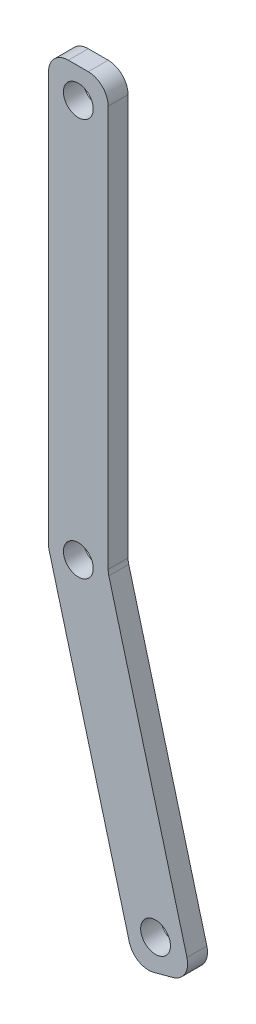
SolidWorks part; units mm, degrees
material "ABS"
ref_plane "Plan de face" through (0, 0, 0) normal (0, 0, 1) x (1, 0, 0)
ref_plane "Plan de dessus" through (0, 0, 0) normal (0, 1, 0) x (1, 0, 0)
ref_plane "Plan de droite" through (0, 0, 0) normal (1, 0, 0) x (0, 0, -1)
sketch "Esquisse2" plane through (0, 0, 0) normal (0, 0, 1) x (1, 0, 0)
  line L0 (0, 0) -> (0, -5.5342) construction
  line L1 (-3, -23) -> (3, -23)
  line L2 (-3, -23) -> (-3, 23)
  line L3 (-3, 23) -> (3, 23)
  line L4 (3, -23) -> (3, 23)
  line L5 (-3, -23) -> (3, 23) construction
  line L6 (-3, 23) -> (3, -23) construction
  line L7 (0, -20) -> (8.541, -51.8756)
  line L8 (5.6433, -52.652) -> (11.4388, -51.0991)
  line L9 (11.4388, -51.0991) -> (3, -19.605)
  line L10 (5.6433, -52.652) -> (-3, -20.395)
  circle A0 centre (0, 20) radius 1.5
  circle A1 centre (0, -20) radius 1.5
  circle A2 centre (7.7646, -48.9778) radius 1.5
  point P0 (0, 0)
  point P15 (8.541, -51.8756)
  dimension "D3" = 3
  dimension "D4" = 0
  dimension "D5" = 3
  dimension "D6" = 3
  dimension "D7" = 3
  dimension "D9" = 3
  dimension "D1" = 40
  dimension "D2" = 6
  dimension "D8" = 165
  dimension "D10" = 6
  dimension "D11" = 3
  dimension "D12" = 30
extrude "Boss.-Extru.3" add sketch "Esquisse2" along normal blind 2
fillet "Congé3" radius 2 6 edges at (5.6433, -52.652, 1) (11.4388, -51.0991, 1) (-3, -20.395, 1) (3, -19.605, 1) (-3, 23, 1) (3, 23, 1)
